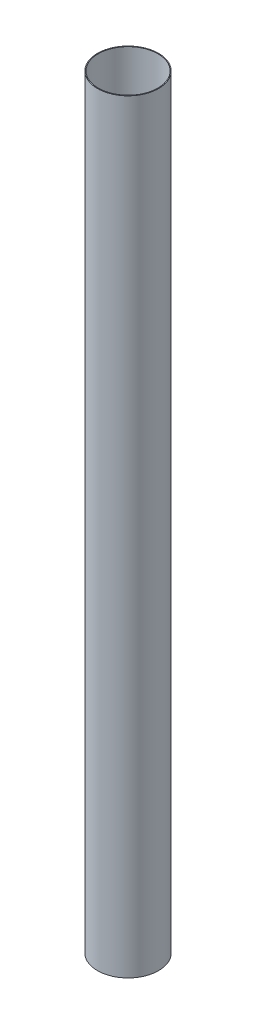
SolidWorks part; units mm, degrees
material "Wildman Fiberglass"
ref_plane "Front Plane" through (0, 0, 0) normal (0, 0, 1) x (1, 0, 0)
ref_plane "Top Plane" through (0, 0, 0) normal (0, 1, 0) x (1, 0, 0)
ref_plane "Right Plane" through (0, 0, 0) normal (1, 0, 0) x (0, 0, -1)
sketch "Sketch1" plane through (0, 0, 0) normal (0, 1, 0) x (1, 0, 0)
  circle A0 centre (0, 0) radius 49.53
  circle A1 centre (0, 0) radius 50.8
  dimension "D1" = 101.6
  dimension "D2" = 99.06
extrude "Boss-Extrude1" add sketch "Sketch1" along normal blind 1270
equation "\"Length\"= 50"
equation "\"D1@Boss-Extrude1\"=\"Length\""
